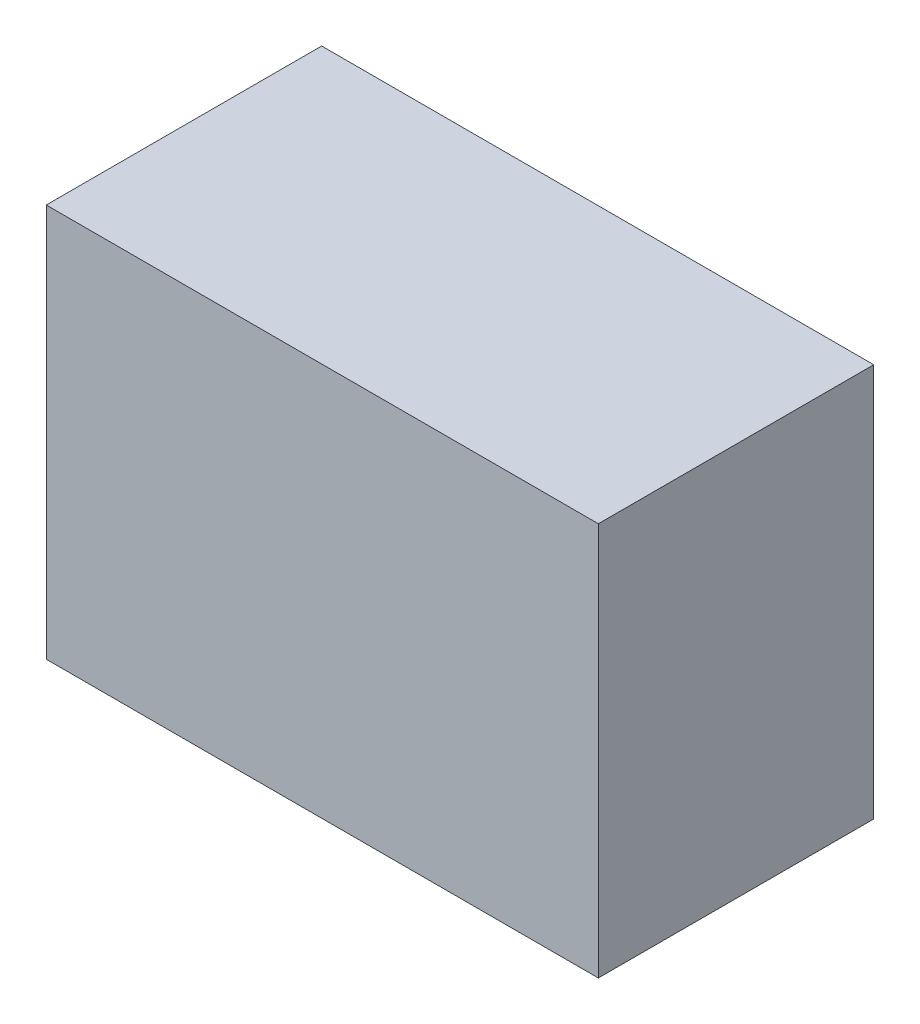
SolidWorks part; units mm, degrees
ref_plane "Front Plane" through (0, 0, 0) normal (0, 0, 1) x (1, 0, 0)
ref_plane "Top Plane" through (0, 0, 0) normal (0, 1, 0) x (1, 0, 0)
ref_plane "Right Plane" through (0, 0, 0) normal (1, 0, 0) x (0, 0, -1)
sketch "Sketch1" plane through (0, 0, 0) normal (0, 0, 1) x (1, 0, 0)
  line L0 (0, 0) -> (0, 1.75) construction
  line L1 (-8.42, 1.75) -> (8.42, 1.75)
  line L2 (-8.42, 1.75) -> (-8.42, -10.25)
  line L3 (-8.42, -10.25) -> (8.42, -10.25)
  line L4 (8.42, 1.75) -> (8.42, -10.25)
  dimension "D1" = 1.75
  dimension "D2" = 12
  dimension "D3" = 16.84
extrude "Boss-Extrude1" add sketch "Sketch1" along normal blind 8.4
sketch "Sketch2" plane through (0, -10.25, 0) normal (0, -1, 0) x (1, 0, 0)
  line L0 (0, 0) -> (0, 6.9) construction
  line L1 (-8.42, 0) -> (8.42, 0) construction
  line L2 (7.42, 6.9) -> (-7.42, 6.9)
  line L3 (-7.42, 6.9) -> (-7.42, 1.7)
  line L4 (-8.42, 8.4) -> (-8.42, 0) construction
  line L5 (-7.42, 1.7) -> (-6.82, 1.7)
  line L6 (-8.42, 8.4) -> (8.42, 8.4) construction
  line L7 (-8.42, 0.7) -> (0, 0.7) construction
  line L8 (-6.82, 1.7) -> (-2.2733, 1.7) construction
  line L9 (7.42, 1.7) -> (6.82, 1.7)
  line L10 (7.42, 6.9) -> (7.42, 1.7)
  arc A0 (-6.82, 1.7) -> (-2.2733, 1.7) centre (-4.5467, 3.784) ccw
  arc A1 (-2.2733, 1.7) -> (2.2733, 1.7) centre (0, 3.784) ccw
  arc A2 (6.82, 1.7) -> (2.2733, 1.7) centre (4.5467, 3.784) cw
  point P10 (-3.2733, 1.2)
  dimension "D1" = 1
  dimension "D2" = 1
  dimension "D3" = 1.5
  dimension "D4" = 0.6
  dimension "D5" = 0.7
extrude "Cut-Extrude1" cut sketch "Sketch2" against normal offset from surface (8 mm away) 4 up to face at (0, 1.75, 4.2)
